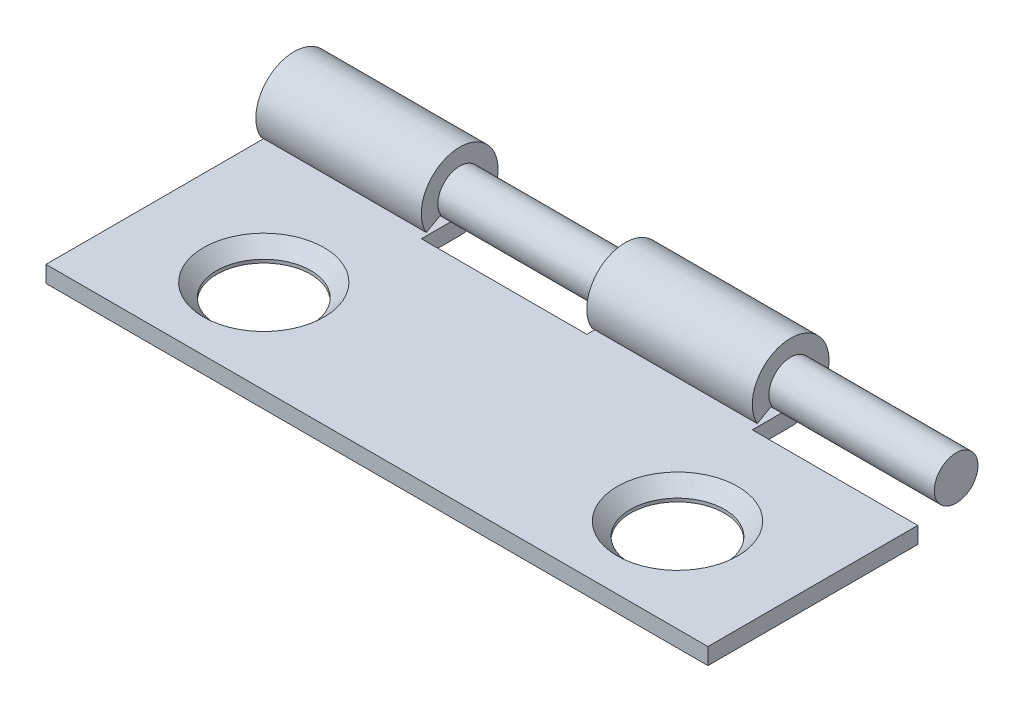
SolidWorks part; units mm, degrees
ref_plane "Front Plane" through (0, 0, 0) normal (0, 0, 1) x (1, 0, 0)
ref_plane "Top Plane" through (0, 0, 0) normal (0, 1, 0) x (1, 0, 0)
ref_plane "Right Plane" through (0, 0, 0) normal (1, 0, 0) x (0, 0, -1)
sketch "Sketch1" plane through (0, 0, 0) normal (0, 1, 0) x (1, 0, 0)
  line L0 (-12.7, 0) -> (12.7, 0) construction
  line L1 (-12.7, -9.525) -> (-12.7, 9.525) construction
  line L2 (-12.7, -9.525) -> (-7.9248, -9.525) construction
  line L4 (-7.9248, -9.525) -> (7.9502, -9.525) construction
  line L5 (12.7254, -9.525) -> (12.7254, -5.9436) construction
  line L6 (7.9502, -9.525) -> (12.7254, -9.525) construction
  line L7 (-12.7, 9.525) -> (-7.9248, 9.525) construction
  line L8 (-7.9248, 9.525) -> (7.9502, 9.525) construction
  line L9 (7.9502, 9.525) -> (23.8252, 9.525) construction
  line L10 (23.8252, 9.525) -> (28.6004, 9.525) construction
  line L11 (7.9502, -8.255) -> (7.9502, -3.6322) construction
  line L12 (7.9502, -5.9436) -> (12.7254, -5.9436) construction
  point P3 (7.9502, -7.747)
  point P4 (0, 0)
  point P8 (-12.7, 0)
  point P17 (-6.35, 0)
  point P21 (7.9502, -5.9436)
  dimension "Frame Leaf Height" = 25.4
  dimension "Overall Width" = 19.05
  dimension "Hole to End 1" = 4.7752
  dimension "Hole to End 2" = 4.7752
  dimension "D1" = 4.7752
  dimension "D2" = 4.7752
  dimension "D4" = 15.875
  dimension "D6" = 15.875
  dimension "Knuckle Length" = 6.35
  dimension "Hole Chamfer Dia" = 4.6228
  dimension "Hole Center to Pin" = 5.9436
  dimension "Door Leaf Height" = 25.4254
  dimension "Mounting Hole Diameter" = 3.6068
  dimension "D3" = 15.875
  dimension "Frame Leaf Width" = 9.525
  dimension "Door Leaf Width" = 9.525
sketch "Sketch2" plane through (0, 0, 0) normal (1, 0, 0) x (0, 0, -1)
  line L2 (0, -1.4732) -> (0, -0.8382) construction
  line L4 (0, 0.8382) -> (0, -0.8382) construction
  point P8 (0, 0)
  dimension "Leaf Thickness" = 0.635
  dimension "Pin Diameter" = 1.6764
sketch "Sketch3" plane through (0, 0, 0) normal (1, 0, 0) x (0, 0, -1)
  line L3 (0, 0) -> (-1.4732, -0.8382) construction
  line L4 (0, -1.4732) -> (-9.525, -1.4732)
  line L5 (-9.525, -1.4732) -> (-9.525, -0.8382)
  line L7 (-9.525, -0.8382) -> (0, -0.8382)
  line L8 (-9.525, 0) -> (9.525, 0) construction
  line L9 (-0.7285, -0.4145) -> (-1.2805, -0.7285)
  line L11 (-1.4732, 0) -> (-1.4732, -0.8382) construction
  circle A4 centre (0, 0) radius 0.8382 construction
  circle A5 centre (0, 0) radius 1.4732 construction
  arc A8 (-0.7285, -0.4145) -> (0, -0.8382) centre (0, 0) cw
  arc A9 (-1.2805, -0.7285) -> (0, -1.4732) centre (0, 0) cw
  point P0 (-1.2805, -0.7285)
  point P13 (-0.7285, -0.4145)
extrude "Boss-Extrude1" add sketch "Sketch3" along normal mid plane 25.4
sketch "Sketch4" plane through (0, 0, 0) normal (0, 1, 0) x (1, 0, 0)
  line L0 (-12.7, -1.4732) -> (12.7, -1.4732) construction
  line L1 (-12.7, -1.4732) -> (12.7, -1.4732) construction
  line L2 (12.7, 1.4732) -> (-12.7, 1.4732) construction
  line L3 (12.7, 1.4732) -> (-12.7, 1.4732) construction
  line L4 (-6.35, -1.4732) -> (-6.35, 1.4732)
  line L6 (-6.35, 1.4732) -> (0, 1.4732)
  line L7 (0, -1.4732) -> (-6.35, -1.4732)
  line L8 (0, 1.4732) -> (0, -1.4732)
  point P8 (-6.35, 0)
  dimension "D1" = 6.35
extrude "Cut-Extrude1" cut sketch "Sketch4" against normal through all both and the other way through all
pattern_linear "LPattern1" count 6 spacing 12.7 along (1, 0, 0) of "Cut-Extrude1"
sketch "Sketch5" plane through (0, -0.8382, 0) normal (0, 1, 0) x (1, 0, 0)
  line L0 (7.9502, -5.9436) -> (-7.9248, -5.9436) construction
  line L1 (0, -5.9436) -> (0, -9.525) construction
  line L2 (-7.9248, -5.9436) -> (-7.9248, -9.525) construction
  line L3 (12.7, -9.525) -> (-12.7, -9.525) construction
  circle A0 centre (7.9502, -5.9436) radius 2.3114
  circle A2 centre (-7.9248, -5.9436) radius 2.3114
extrude "Cut-Extrude2" cut sketch "Sketch5" against normal through all draft 45
sketch "Sketch9" plane through (0, 0, 0) normal (0, 1, 0) x (1, 0, 0)
  circle A0 centre (7.9502, -5.9436) radius 1.8034
  circle A2 centre (-7.9248, -5.9436) radius 1.8034
  dimension "D1" = 3.6068
extrude "Cut-Extrude3" cut sketch "Sketch9" against normal through all both and the other way through all
sketch "Sketch6" plane through (0, 0, 0) normal (1, 0, 0) x (0, 0, -1)
  circle A0 centre (0, 0) radius 0.8382
  dimension "D1" = 1.6764
extrude "Boss-Extrude2" add sketch "Sketch6" along normal mid plane 25.4 separate body
equation "\"D1@Sketch1\"=\"Hole to End 1@Sketch1\""
equation "\"D2@Sketch1\"=\"Hole to End 2@Sketch1\""
equation "\"D6@Sketch1\"=\"D4@Sketch1\""
equation "\"D1@Boss-Extrude1\" = \"Frame Leaf Height@Sketch1\""
equation "\"D1@Sketch4\"=\"Knuckle Length@Sketch1\""
equation "\"D3@LPattern1\"=\"Knuckle Length@Sketch1\"*2"
equation "\"D1@Sketch6\"=\"Pin Diameter@Sketch2\""
equation "\"D1@Boss-Extrude2\" = \"Frame Leaf Height@Sketch1\""
equation "\"Knuckle Length@Sketch1\"=\"Frame Leaf Height@Sketch1\" / 4"
equation "\"Hole to End 2@Sketch1\"=\"Hole to End 1@Sketch1\""
equation "\"D1@Sketch9\"=\"Mounting Hole Diameter@Sketch1\""
equation "\"Hole Chamfer Dia@Sketch1\"=\"Mounting Hole Diameter@Sketch1\"+.04"
